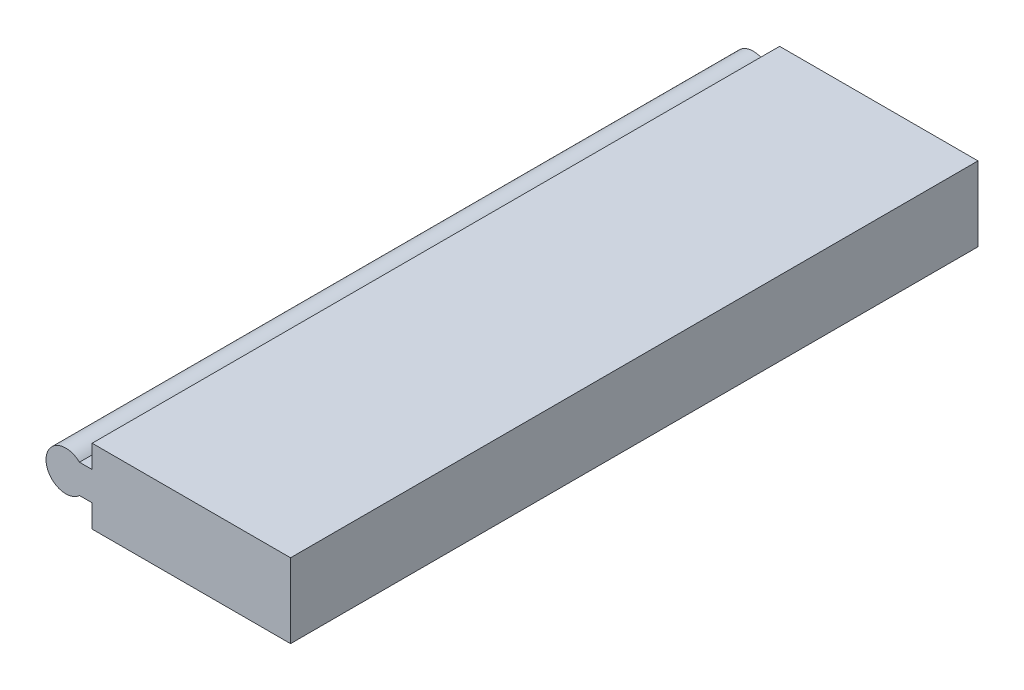
SolidWorks part; units mm, degrees
ref_plane "Front Plane" through (0, 0, 0) normal (0, 0, 1) x (1, 0, 0)
ref_plane "Top Plane" through (0, 0, 0) normal (0, 1, 0) x (1, 0, 0)
ref_plane "Right Plane" through (0, 0, 0) normal (1, 0, 0) x (0, 0, -1)
sketch "Sketch1" plane through (0, 0, 0) normal (0, 0, 1) x (1, 0, 0)
  line L0 (1.3737, 1.4536) -> (2.6516, 1.4536)
  line L1 (2.6516, 1.4536) -> (2.6516, 3.75)
  line L2 (2.6516, 3.75) -> (22.6516, 3.75)
  line L3 (0, 0) -> (1.8849, 0) construction
  line L4 (1.3737, -1.4536) -> (2.6516, -1.4536)
  line L5 (2.6516, -1.4536) -> (2.6516, -3.75)
  line L6 (2.6516, -3.75) -> (22.6516, -3.75)
  line L7 (22.6516, 3.75) -> (22.6516, -3.75)
  arc A0 (1.3737, 1.4536) -> (1.3737, -1.4536) centre (0, 0) ccw
  point P12 (0, 0)
  point P13 (0, 0)
  point P14 (0, 0)
  point P15 (0, 0)
  point P16 (0, 0)
  dimension "D1" = 2
  dimension "D2" = 7.5
  dimension "D3" = 20
extrude "Boss-Extrude1" add sketch "Sketch1" along normal blind 69.3
